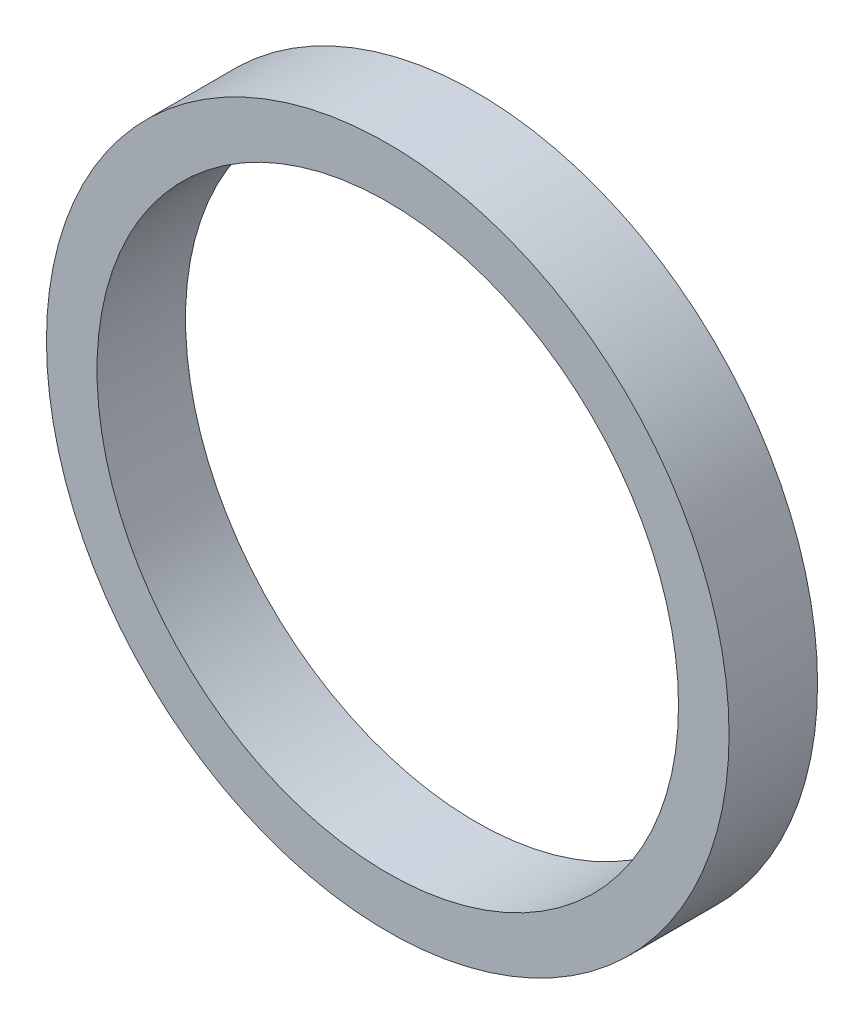
SolidWorks part; units mm, degrees
ref_plane "Plan de face" through (0, 0, 0) normal (0, 0, 1) x (1, 0, 0)
ref_plane "Plan de dessus" through (0, 0, 0) normal (0, 1, 0) x (1, 0, 0)
ref_plane "Plan de droite" through (0, 0, 0) normal (1, 0, 0) x (0, 0, -1)
sketch "Esquisse1" plane through (0, 0, 0) normal (0, 0, 1) x (1, 0, 0)
  circle A0 centre (0, 0) radius 23
  circle A1 centre (0, 0) radius 27
  dimension "D1" = 4
  dimension "D2" = 46
extrude "BASE" add sketch "Esquisse1" along normal blind 7
